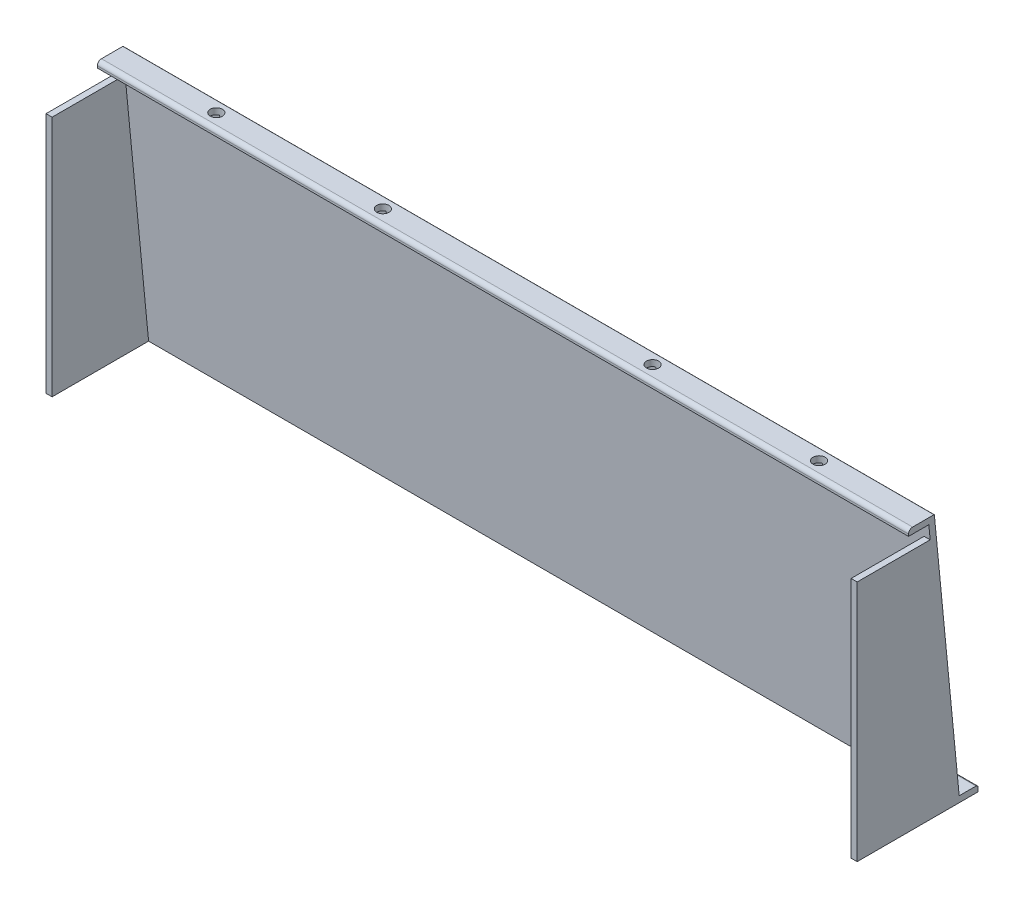
SolidWorks part; units mm, degrees
material "PMMA"
ref_plane "前视基准面" through (0, 0, 0) normal (0, 0, 1) x (1, 0, 0)
ref_plane "上视基准面" through (0, 0, 0) normal (0, 1, 0) x (1, 0, 0)
ref_plane "右视基准面" through (0, 0, 0) normal (1, 0, 0) x (0, 0, -1)
sketch "草图1" plane through (0, 0, 0) normal (1, 0, 0) x (0, 0, -1)
  line L0 (0, 4.4903) -> (5.69, -54.1397)
  line L1 (0, -54.1397) -> (5.69, -54.1397) construction
  line L2 (7.0515, -52.6397) -> (7.4872, -57.1297)
  line L3 (6.1258, -58.6297) -> (12.1258, -58.6297)
  line L6 (1.3938, 5.6574) -> (7.0515, -52.6397)
  line L7 (0, 4.4903) -> (-5, 4.4903)
  line L8 (-5, 4.4903) -> (-5, 4.9903)
  line L9 (-4, 5.9903) -> (1.2707, 5.9903)
  line L10 (1.3938, 5.6574) -> (1.3702, 5.8999)
  line L11 (31.5911, -58.6297) -> (-90.1574, -58.6297) construction
  line L12 (5.69, -54.1397) -> (6.1258, -58.6297)
  line L13 (12.1258, -58.6297) -> (12.1258, -57.6297)
  line L14 (11.6258, -57.1297) -> (7.4872, -57.1297)
  arc A0 (12.1258, -57.6297) -> (11.6258, -57.1297) centre (11.6258, -57.6297) ccw
  arc A1 (-5, 4.9903) -> (-4, 5.9903) centre (-4, 4.9903) cw
  arc A2 (1.3702, 5.8999) -> (1.2707, 5.9903) centre (1.2707, 5.8903) ccw
  point P11 (12.1258, -57.1297)
  point P16 (-5, 5.9903)
  dimension "D9" = 1
  dimension "D10" = 0.1
  dimension "D4" = 0.5
  dimension "D1" = 58.63
  dimension "D2" = 5.69
  dimension "D3" = 6
  dimension "D5" = 1.5
  dimension "D6" = 5
  dimension "D7" = 1.5
  dimension "D11" = 1.5
extrude "凸台-拉伸1" add sketch "草图1" along normal blind 165
sketch "草图2" plane through (0, 5.9903, 0) normal (0, 1, 0) x (1, 0, 0)
  line L0 (82.5, 1.2707) -> (82.5, -1.9792) construction
  line L3 (165, 1.2707) -> (0, 1.2707) construction
  line L4 (82.5, 11.6471) -> (82.5, 8.3971) construction
  circle A0 centre (156.808, -1.3646) radius 1.5
  circle A1 centre (115.75, -1.3646) radius 1.5
  circle A2 centre (49.25, -1.3646) radius 1.5
  circle A3 centre (8.192, -1.3646) radius 1.5
  circle A4 centre (8.192, 9.0117) radius 1.5
  circle A5 centre (156.808, 9.0117) radius 1.5
  circle A6 centre (115.75, 9.0117) radius 1.5
  circle A7 centre (49.25, 9.0117) radius 1.5
  dimension "D1" = 3
  dimension "D2" = 3
extrude "切除-拉伸2" cut sketch "草图2" against normal blind 66
sketch "草图3" plane through (165, 0, 0) normal (1, 0, 0) x (0, 0, -1)
  line L0 (0.3296, 1.0939) -> (-17.6704, 1.0939)
  line L1 (0, 4.4903) -> (6.1258, -58.6297) construction
  line L2 (-17.6704, 1.0939) -> (-17.6704, -58.6297)
  line L3 (6.1258, -58.6297) -> (-17.6704, -58.6297)
  line L4 (0.3296, 1.0939) -> (6.1258, -58.6297)
  dimension "D1" = 18
extrude "凸台-拉伸2" add sketch "草图3" against normal blind 1.5
ref_plane "基准面1" through (82.5, 0, 0) normal (1, 0, 0) x (0, 0, -1)
sketch "草图5" plane through (0, 0, 0) normal (-1, 0, 0) x (0, 0, 1)
  line L0 (-1.3702, 5.8999) -> (-7.4872, -57.1297)
  line L1 (-7.4872, -57.1297) -> (-11.6258, -57.1297)
  line L2 (-12.1258, -57.6297) -> (-12.1258, -58.6297)
  line L3 (-12.1258, -58.6297) -> (-6.1258, -58.6297)
  line L4 (-6.1258, -58.6297) -> (0, 4.4903)
  line L5 (0, 4.4903) -> (-6.1258, -58.6297) construction
  line L6 (0, 4.4903) -> (5, 4.4903)
  line L7 (5, 4.4903) -> (5, 4.9903)
  line L8 (4, 5.9903) -> (-1.2707, 5.9903)
  arc A0 (5, 4.9903) -> (4, 5.9903) centre (4, 4.9903) ccw construction
  arc A1 (-1.2707, 5.9903) -> (-1.3702, 5.8999) centre (-1.2707, 5.8903) ccw
  arc A2 (-1.2707, 5.9903) -> (-1.3702, 5.8999) centre (-1.2707, 5.8903) ccw construction
  arc A3 (5, 4.9903) -> (4, 5.9903) centre (4, 4.9903) ccw
  arc A4 (-11.6258, -57.1297) -> (-12.1258, -57.6297) centre (-11.6258, -57.6297) ccw
  arc M1 (-1.2707, 5.9903) -> (-1.3702, 5.8999) centre (-1.2707, 5.8903) ccw
  line M2 (-1.3702, 5.8999) -> (-7.4872, -57.1297)
  line M3 (-7.4872, -57.1297) -> (-11.6258, -57.1297)
  arc M4 (-11.6258, -57.1297) -> (-12.1258, -57.6297) centre (-11.6258, -57.6297) ccw
  line M5 (-12.1258, -57.6297) -> (-12.1258, -58.6297)
  line M6 (-12.1258, -58.6297) -> (-6.1258, -58.6297)
  line M7 (-6.1258, -58.6297) -> (0, 4.4903)
  line M8 (0, 4.4903) -> (5, 4.4903)
  line M9 (5, 4.4903) -> (5, 4.9903)
  arc M10 (5, 4.9903) -> (4, 5.9903) centre (4, 4.9903) ccw
  line M11 (4, 5.9903) -> (-1.2707, 5.9903)
extrude "凸台-拉伸3" add sketch "草图5" along normal blind 17.5 contours M11 M1 M2 M3 M4 M5 M6 M7 M8 M9 M10
mirror "镜向2" about plane through (82.5, 0, 0) normal (1, 0, 0) of "凸台-拉伸3"
sketch "草图6" plane through (182.5, 0, 0) normal (1, 0, 0) x (0, 0, -1)
  line L0 (0.3296, 1.0939) -> (-17.6704, 1.0939)
  line L1 (-17.6704, 1.0939) -> (-17.6704, -58.6297)
  line L2 (-17.6704, -58.6297) -> (6.1258, -58.6297)
  line L3 (6.1258, -58.6297) -> (0.3296, 1.0939)
extrude "凸台-拉伸4" add sketch "草图6" against normal blind 1.5
sketch "草图7" plane through (165, 0, 0) normal (1, 0, 0) x (0, 0, -1)
  line L0 (0.3296, 1.0939) -> (6.3829, -61.2798)
  line L1 (6.3829, -61.2798) -> (-18.871, -61.2798)
  line L2 (-18.871, -61.2798) -> (-18.871, 1.0939)
  line L3 (-18.871, 1.0939) -> (0.3296, 1.0939)
extrude "切除-拉伸3" cut sketch "草图7" against normal blind 1.5
mirror "镜向4" about plane through (82.5, 0, 0) normal (1, 0, 0) of "凸台-拉伸4"
